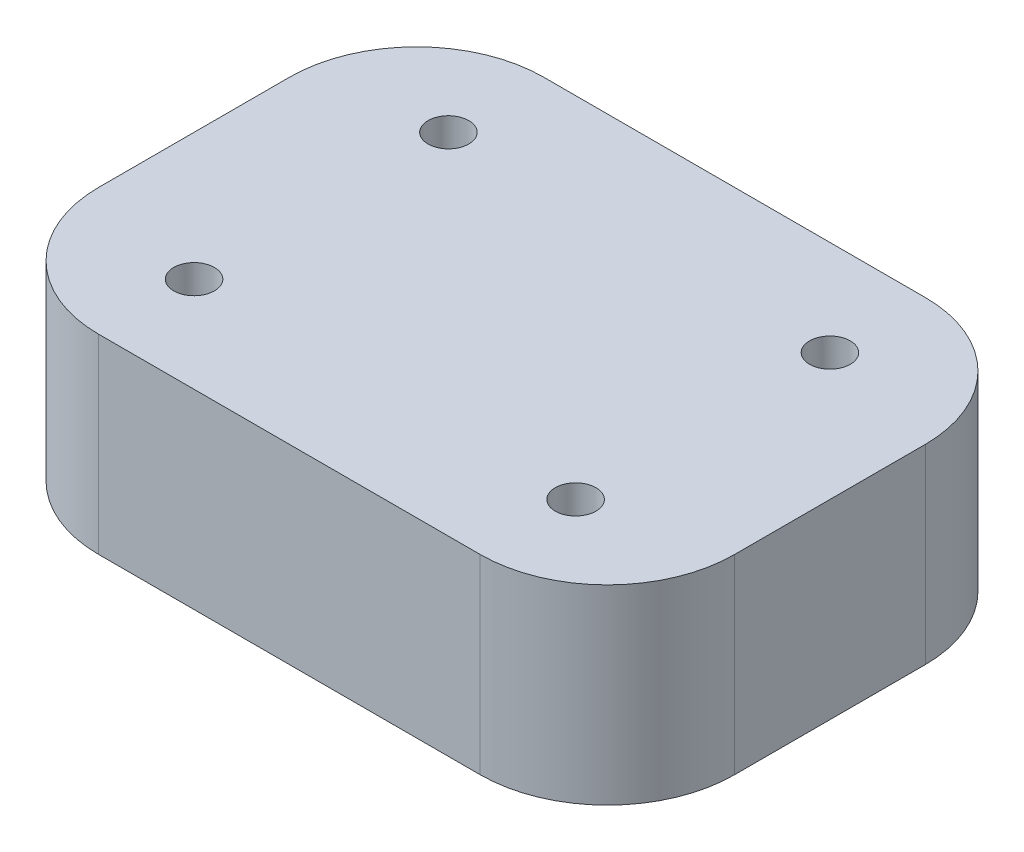
SolidWorks part; units mm, degrees
ref_plane "Front Plane" through (0, 0, 0) normal (0, 0, 1) x (1, 0, 0)
ref_plane "Top Plane" through (0, 0, 0) normal (0, 1, 0) x (1, 0, 0)
ref_plane "Right Plane" through (0, 0, 0) normal (1, 0, 0) x (0, 0, -1)
sketch "Sketch1" plane through (0, 0, 0) normal (0, 1, 0) x (1, 0, 0)
  line L0 (0, 17.5) -> (50, 17.5) construction
  line L1 (0, 0) -> (50, 0)
  line L2 (0, 0) -> (0, 35)
  line L3 (0, 35) -> (50, 35)
  line L4 (50, 0) -> (50, 35)
  line L5 (0, 27.5) -> (50, 27.5) construction
  circle A0 centre (10, 27.5) radius 1.6
  circle A1 centre (40, 27.5) radius 1.6
  circle A2 centre (40, 7.5) radius 1.6
  circle A3 centre (10, 7.5) radius 1.6
  point P11 (0, 0)
  point P12 (7, 30)
  point P15 (0, 0)
  point P16 (43, 30)
  dimension "D3" = 10
  dimension "D4" = 10
  dimension "D5" = 3.2
  dimension "D1" = 35
  dimension "D2" = 50
  dimension "D6" = 10
extrude "Boss-Extrude1" add sketch "Sketch1" along normal blind 15
fillet "Fillet1" radius 10 4 edges at (0, 7.5, -35) (50, 7.5, -35) (50, 7.5, 0) (0, 7.5, 0)
